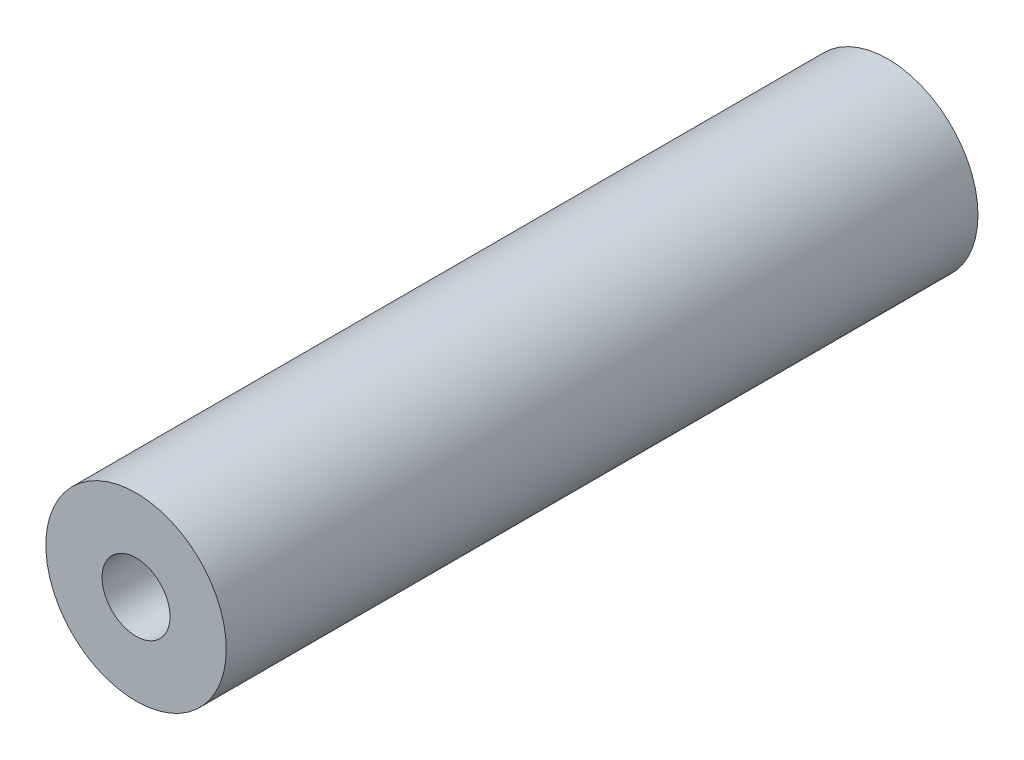
SolidWorks part; units mm, degrees
material "Polyurethane Foam Rigid"
ref_plane "Front Plane" through (0, 0, 0) normal (0, 0, 1) x (1, 0, 0)
ref_plane "Top Plane" through (0, 0, 0) normal (0, 1, 0) x (1, 0, 0)
ref_plane "Right Plane" through (0, 0, 0) normal (1, 0, 0) x (0, 0, -1)
sketch "Sketch1" plane through (0, 0, 0) normal (0, 0, 1) x (1, 0, 0)
  circle A0 centre (0, 0) radius 30
  circle A1 centre (0, 0) radius 11.3
extrude "Boss-Extrude1" add sketch "Sketch1" along normal blind 250
